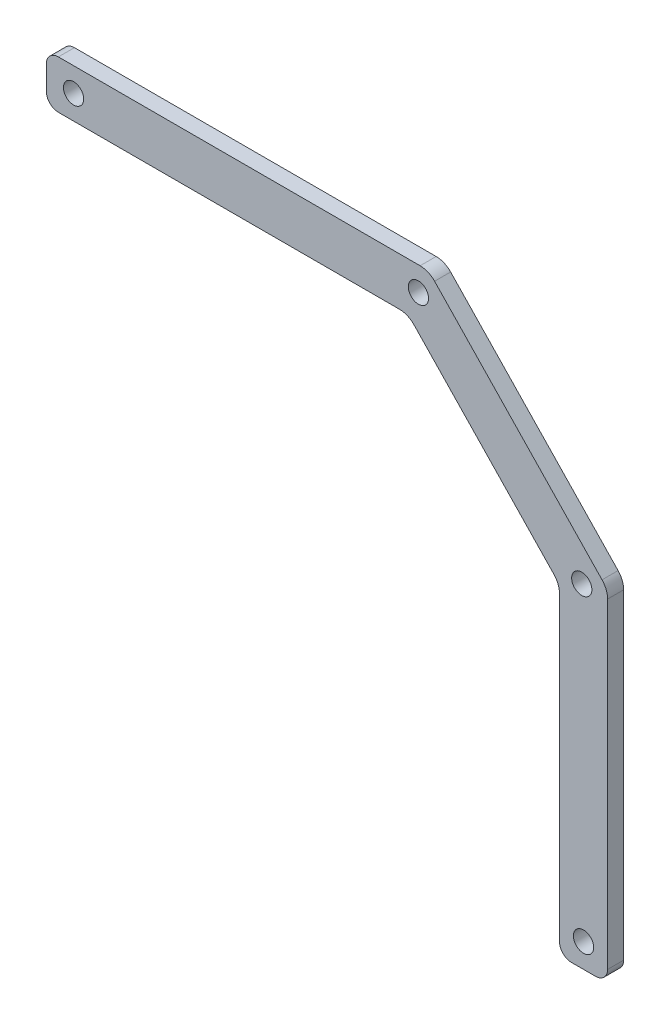
SolidWorks part; units mm, degrees
material "Thornel Mat VMA"
ref_plane "前视基准面" through (0, 0, 0) normal (0, 0, 1) x (1, 0, 0)
ref_plane "上视基准面" through (0, 0, 0) normal (0, 1, 0) x (1, 0, 0)
ref_plane "右视基准面" through (0, 0, 0) normal (1, 0, 0) x (0, 0, -1)
other "Configuration Table"
sketch "草图1" plane through (0, 0, 0) normal (0, 0, 1) x (1, 0, 0)
  line L1 (-70, -70) -> (70, -70)
  line L2 (-70, -70) -> (-70, 70)
  line L3 (-70, 70) -> (70, 70)
  line L4 (70, -70) -> (70, 70)
  line L5 (-70, -70) -> (70, 70) construction
  line L6 (-70, 70) -> (70, -70) construction
  point P0 (0, 0)
  dimension "D1" = 140
  dimension "D2" = 140
extrude "凸台-拉伸1" add sketch "草图1" along normal mid plane 4
sketch "草图2" plane through (0, 0, 2) normal (0, 0, 1) x (1, 0, 0)
  line L0 (-70, -70) -> (70, -70) construction
  line L1 (70, -70) -> (70, 70) construction
  circle A0 centre (64, -64) radius 2.525
  dimension "D1" = 5.05
  dimension "D2" = 6
  dimension "D3" = 6
extrude "切除-拉伸1" cut sketch "草图2" against normal mid plane 24
sketch "草图3" plane through (0, 0, 2) normal (0, 0, 1) x (1, 0, 0)
  circle A0 centre (-63.2139, 55.65) radius 2.1 construction
  circle A1 centre (22.8047, 55.6227) radius 2.1 construction
  circle A2 centre (63.5512, 13.0736) radius 2.1 construction
  circle A3 centre (-63.2139, 55.65) radius 2.1 construction
  circle A4 centre (22.8047, 55.6227) radius 2.1 construction
  circle A5 centre (63.5512, 13.0736) radius 2.1 construction
  circle A6 centre (63.5512, 13.0736) radius 2.525
  circle A7 centre (22.8047, 55.6227) radius 2.525
  circle A8 centre (-63.2139, 55.65) radius 2.525
  circle A9 centre (64, -64) radius 2.525 construction
  circle A10 centre (64, -64) radius 2.525 construction
extrude "切除-拉伸2" cut sketch "草图3" against normal mid plane 34
sketch "草图4" plane through (0, 0, -2) normal (0, 0, -1) x (-1, 0, 0)
  line L0 (-58, -70) -> (-58, 10.1954)
  line L1 (70, -70) -> (-70, -70) construction
  line L2 (-58, 10.1954) -> (-20.2169, 49.65)
  line L3 (-20.2169, 49.65) -> (70, 49.65)
  line L4 (70, 70) -> (70, -70) construction
  line L5 (70, 49.65) -> (70, 61.6227)
  line L6 (70, 61.6227) -> (-25.3664, 61.6227)
  line L7 (-25.3664, 61.6227) -> (-70, 15.0145)
  line L8 (-70, -70) -> (-70, 70) construction
  line L9 (-70, 15.0145) -> (-70, -70)
  line L10 (-70, -70) -> (-58, -70)
  line L11 (-63.5512, 13.0736) -> (-22.8047, 55.6227) construction
  circle A0 centre (-64, -64) radius 2.525 construction
  circle A1 centre (-63.5512, 13.0736) radius 2.525 construction
  circle A2 centre (-22.8047, 55.6227) radius 2.525 construction
  circle A3 centre (63.2139, 55.65) radius 2.525 construction
  dimension "D1" = 6
  dimension "D2" = 6
  dimension "D3" = 6
  dimension "D4" = 6
  dimension "D5" = 6
extrude "切除-拉伸3" cut sketch "草图4" against normal mid plane 44 flip side to cut
fillet "圆角1" radius 3 2 edges at (58, -70, 0) (70, -70, 0)
fillet "圆角2" radius 3 2 edges at (-70, 61.6227, 0) (-70, 49.65, 0)
fillet "圆角3" radius 5 4 edges at (25.3664, 61.6227, 0) (70, 15.0145, 0) (58, 10.1954, 0) (20.2169, 49.65, 0)
equation "\"D5@草图4\"=\"D4@草图4\""
equation "\"D2@草图4\"=\"D4@草图4\""
equation "\"D3@草图4\"=\"D4@草图4\""
equation "\"D1@草图4\"=\"D4@草图4\""
